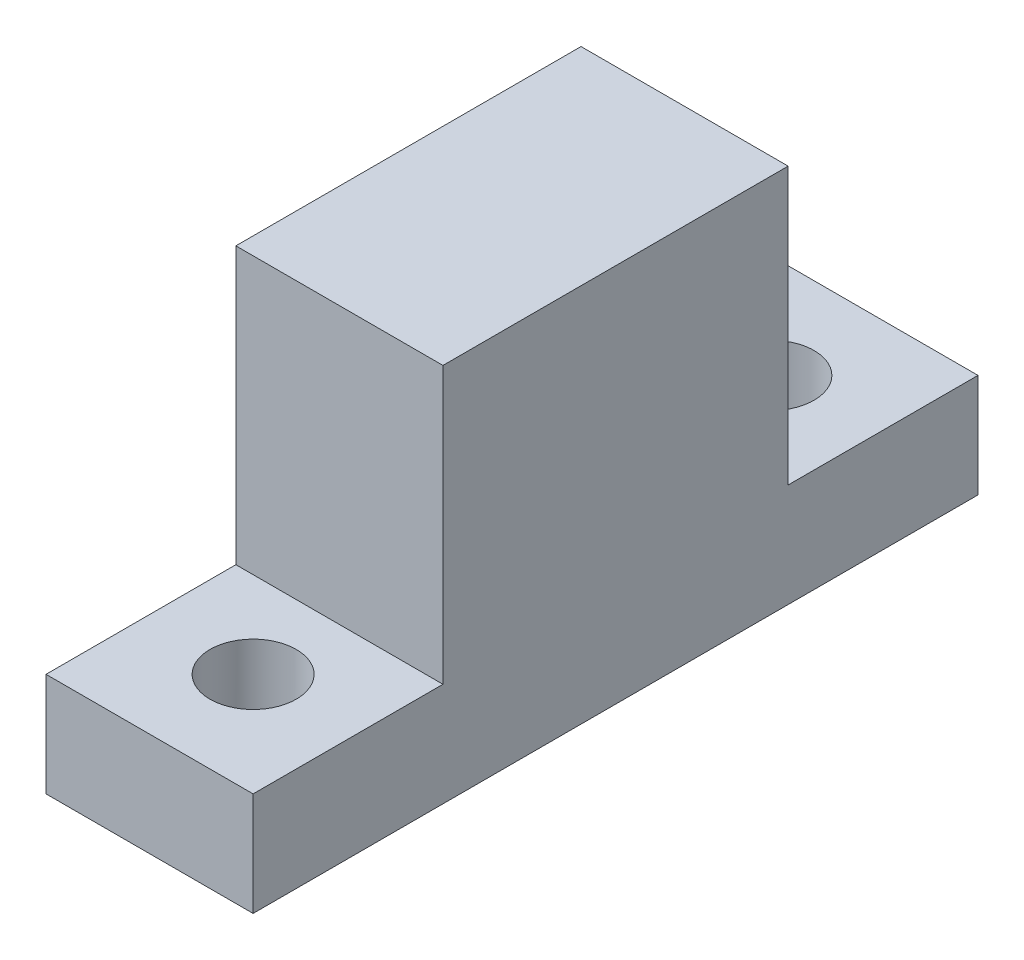
SolidWorks part; units mm, degrees
ref_plane "Front Plane" through (0, 0, 0) normal (0, 0, 1) x (1, 0, 0)
ref_plane "Top Plane" through (0, 0, 0) normal (0, 1, 0) x (1, 0, 0)
ref_plane "Right Plane" through (0, 0, 0) normal (1, 0, 0) x (0, 0, -1)
sketch "Sketch2" plane through (0, 0, 0) normal (0, 1, 0) x (1, 0, 0)
  line L1 (0, 0) -> (6, 0)
  line L2 (0, 0) -> (0, 21)
  line L3 (0, 21) -> (6, 21)
  line L4 (6, 0) -> (6, 21)
  dimension "D1" = 21
  dimension "D2" = 6
extrude "Boss-Extrude1" add sketch "Sketch2" along normal blind 3
sketch "Sketch3" plane through (0, 3, 0) normal (0, 1, 0) x (1, 0, 0)
  line L0 (0, 21) -> (0, 0) construction
  line L1 (0, 15.5) -> (6, 15.5)
  line L2 (0, 15.5) -> (0, 5.5)
  line L3 (0, 5.5) -> (6, 5.5)
  line L4 (6, 15.5) -> (6, 5.5)
  line L5 (6, 0) -> (6, 21) construction
  line L6 (6, 21) -> (0, 21) construction
  dimension "D1" = 10
  dimension "D2" = 5.5
extrude "Boss-Extrude2" add sketch "Sketch3" along normal blind 8
sketch "Sketch4" plane through (0, 3, 0) normal (0, 1, 0) x (1, 0, 0)
  line L0 (6, 21) -> (0, 21) construction
  line L1 (6, 15.5) -> (6, 21) construction
  circle A0 centre (3, 18) radius 1.25
  dimension "D1" = 2.5
  dimension "D2" = 3
  dimension "D3" = 3
sketch "Sketch5" plane through (0, 3, 0) normal (0, 1, 0) x (1, 0, 0)
  line L0 (6, 0) -> (6, 5.5) construction
  line L1 (0, 0) -> (6, 0) construction
  circle A0 centre (3, 3) radius 1.25
  dimension "D1" = 2.5
  dimension "D2" = 3
  dimension "D3" = 3
extrude "Cut-Extrude1" cut sketch "Sketch4" against normal blind 6 contours A0
extrude "Cut-Extrude2" cut sketch "Sketch5" against normal blind 6 contours A0
